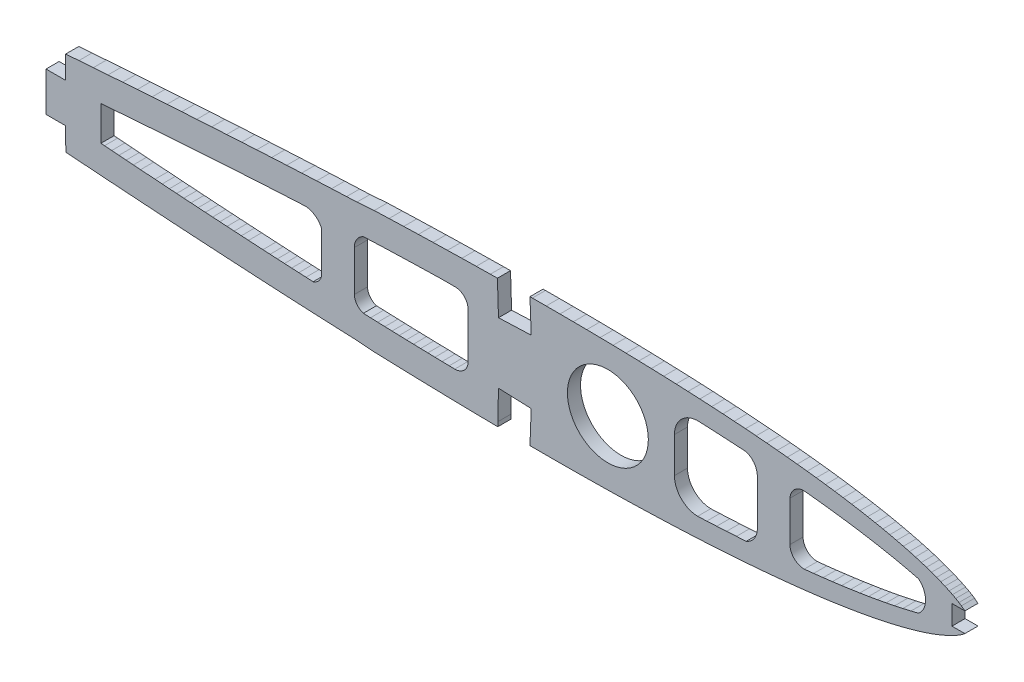
SolidWorks part; units mm, degrees
ref_plane "前视基准面" through (0, 0, 0) normal (0, 0, 1) x (1, 0, 0)
ref_plane "上视基准面" through (0, 0, 0) normal (0, 1, 0) x (1, 0, 0)
ref_plane "右视基准面" through (0, 0, 0) normal (1, 0, 0) x (0, 0, -1)
sketch "Model" plane through (0, 0, 0) normal (0, 0, 1) x (1, 0, 0)
  line L0 (131.5025, 16.1878) -> (129.5305, 16.1878)
  line L1 (129.5305, 16.1878) -> (129.5305, 13.1878)
  line L2 (129.5305, 13.1878) -> (131.5025, 13.1878)
  line L3 (60.157, 24.4938) -> (60.3185, 19.3451)
  line L4 (60.3185, 19.3451) -> (65.3145, 19.5391)
  line L5 (65.3145, 19.5391) -> (65.1226, 24.5339)
  line L6 (60.2125, 4.8817) -> (60.2125, 5.5444)
  line L7 (60.2125, 5.5444) -> (60.3179, 10.0318)
  line L8 (60.3179, 10.0318) -> (65.3139, 9.8388)
  line L9 (65.3139, 9.8388) -> (65.1209, 4.8418)
  line L10 (-5.7395, 21.1711) -> (-3.7144, 21.3221)
  line L11 (-3.7144, 21.3221) -> (-1.5144, 21.4831)
  line L12 (-1.5144, 21.4831) -> (0.7226, 21.6431)
  line L13 (0.7226, 21.6431) -> (2.9586, 21.8011)
  line L14 (2.9586, 21.8011) -> (5.1956, 21.9561)
  line L15 (5.1956, 21.9561) -> (7.4586, 22.1101)
  line L16 (7.4586, 22.1101) -> (9.7206, 22.2601)
  line L17 (9.7206, 22.2601) -> (11.9836, 22.4061)
  line L18 (11.9836, 22.4061) -> (14.2656, 22.5491)
  line L19 (14.2656, 22.5491) -> (16.5466, 22.6871)
  line L20 (16.5466, 22.6871) -> (18.8296, 22.8221)
  line L21 (18.8296, 22.8221) -> (21.1186, 22.9561)
  line L22 (21.1186, 22.9561) -> (23.4086, 23.0871)
  line L23 (23.4086, 23.0871) -> (25.6986, 23.2141)
  line L24 (25.6986, 23.2141) -> (27.9886, 23.3351)
  line L25 (27.9886, 23.3351) -> (30.2776, 23.4511)
  line L26 (30.2776, 23.4511) -> (32.5676, 23.5621)
  line L27 (32.5676, 23.5621) -> (34.8496, 23.6671)
  line L28 (34.8496, 23.6671) -> (37.1306, 23.7671)
  line L29 (37.1306, 23.7671) -> (38.7147, 23.833)
  line L30 (38.7147, 23.833) -> (41.3505, 24.0328)
  line L31 (41.3505, 24.0328) -> (43.6135, 24.1108)
  line L32 (43.6135, 24.1108) -> (45.8505, 24.1828)
  line L33 (45.8505, 24.1828) -> (48.0865, 24.2488)
  line L34 (48.0865, 24.2488) -> (50.3235, 24.3078)
  line L35 (50.3235, 24.3078) -> (52.5235, 24.3608)
  line L36 (52.5235, 24.3608) -> (54.7235, 24.4078)
  line L37 (54.7235, 24.4078) -> (56.9235, 24.4478)
  line L38 (56.9235, 24.4478) -> (59.0795, 24.4808)
  line L39 (59.0795, 24.4808) -> (60.157, 24.4938)
  line L40 (65.1226, 24.5339) -> (65.4935, 24.5358)
  line L41 (65.4935, 24.5358) -> (67.5965, 24.5398)
  line L42 (67.5965, 24.5398) -> (69.6995, 24.5358)
  line L43 (69.6995, 24.5358) -> (71.7415, 24.5248)
  line L44 (71.7415, 24.5248) -> (73.7825, 24.5058)
  line L45 (73.7825, 24.5058) -> (75.8245, 24.4788)
  line L46 (75.8245, 24.4788) -> (77.7965, 24.4448)
  line L47 (77.7965, 24.4448) -> (79.7685, 24.4018)
  line L48 (79.7685, 24.4018) -> (81.7395, 24.3498)
  line L49 (81.7395, 24.3498) -> (83.6355, 24.2918)
  line L50 (83.6355, 24.2918) -> (85.5305, 24.2248)
  line L51 (85.5305, 24.2248) -> (87.4255, 24.1488)
  line L52 (87.4255, 24.1488) -> (89.2365, 24.0668)
  line L53 (89.2365, 24.0668) -> (91.0465, 23.9758)
  line L54 (91.0465, 23.9758) -> (92.8565, 23.8748)
  line L55 (92.8565, 23.8748) -> (94.5765, 23.7688)
  line L56 (94.5765, 23.7688) -> (96.2945, 23.6538)
  line L57 (96.2945, 23.6538) -> (98.0125, 23.5268)
  line L58 (98.0125, 23.5268) -> (99.6345, 23.3978)
  line L59 (99.6345, 23.3978) -> (101.2535, 23.2578)
  line L60 (101.2535, 23.2578) -> (102.8735, 23.1068)
  line L61 (102.8735, 23.1068) -> (104.3905, 22.9548)
  line L62 (104.3905, 22.9548) -> (105.9065, 22.7928)
  line L63 (105.9065, 22.7928) -> (107.4205, 22.6188)
  line L64 (107.4205, 22.6188) -> (108.8265, 22.4458)
  line L65 (108.8265, 22.4458) -> (110.2305, 22.2608)
  line L66 (110.2305, 22.2608) -> (111.6335, 22.0628)
  line L67 (111.6335, 22.0628) -> (112.9235, 21.8688)
  line L68 (112.9235, 21.8688) -> (114.2105, 21.6628)
  line L69 (114.2105, 21.6628) -> (115.4955, 21.4438)
  line L70 (115.4955, 21.4438) -> (116.6655, 21.2318)
  line L71 (116.6655, 21.2318) -> (117.8315, 21.0068)
  line L72 (117.8315, 21.0068) -> (118.9955, 20.7678)
  line L73 (118.9955, 20.7678) -> (120.0385, 20.5388)
  line L74 (120.0385, 20.5388) -> (121.0785, 20.2958)
  line L75 (121.0785, 20.2958) -> (122.1155, 20.0388)
  line L76 (122.1155, 20.0388) -> (123.0305, 19.7978)
  line L77 (123.0305, 19.7978) -> (123.9415, 19.5428)
  line L78 (123.9415, 19.5428) -> (124.8475, 19.2708)
  line L79 (124.8475, 19.2708) -> (125.6295, 19.0188)
  line L80 (125.6295, 19.0188) -> (126.4055, 18.7518)
  line L81 (126.4055, 18.7518) -> (127.1755, 18.4648)
  line L82 (127.1755, 18.4648) -> (127.8215, 18.2068)
  line L83 (127.8215, 18.2068) -> (128.4605, 17.9328)
  line L84 (128.4605, 17.9328) -> (129.0925, 17.6428)
  line L85 (129.0925, 17.6428) -> (129.6015, 17.3938)
  line L86 (129.6015, 17.3938) -> (130.1025, 17.1288)
  line L87 (130.1025, 17.1288) -> (130.5915, 16.8418)
  line L88 (130.5915, 16.8418) -> (130.9655, 16.5968)
  line L89 (130.9655, 16.5968) -> (131.5025, 16.1878)
  line L92 (131.5025, 13.1878) -> (131.3255, 13.0418)
  line L93 (131.3255, 13.0418) -> (130.9655, 12.7788)
  line L94 (130.9655, 12.7788) -> (130.5915, 12.5348)
  line L95 (130.5915, 12.5348) -> (130.1025, 12.2478)
  line L96 (130.1025, 12.2478) -> (129.6015, 11.9828)
  line L97 (129.6015, 11.9828) -> (129.0925, 11.7338)
  line L98 (129.0925, 11.7338) -> (128.4605, 11.4438)
  line L99 (128.4605, 11.4438) -> (127.8215, 11.1698)
  line L100 (127.8215, 11.1698) -> (127.1755, 10.9108)
  line L101 (127.1755, 10.9108) -> (126.4055, 10.6248)
  line L102 (126.4055, 10.6248) -> (125.6295, 10.3568)
  line L103 (125.6295, 10.3568) -> (124.8475, 10.1058)
  line L104 (124.8475, 10.1058) -> (123.9415, 9.8338)
  line L105 (123.9415, 9.8338) -> (123.0305, 9.5788)
  line L106 (123.0305, 9.5788) -> (122.1155, 9.3378)
  line L107 (122.1155, 9.3378) -> (121.0785, 9.0798)
  line L108 (121.0785, 9.0798) -> (120.0385, 8.8378)
  line L109 (120.0385, 8.8378) -> (118.9955, 8.6088)
  line L110 (118.9955, 8.6088) -> (117.8315, 8.3688)
  line L111 (117.8315, 8.3688) -> (116.6655, 8.1448)
  line L112 (116.6655, 8.1448) -> (115.4955, 7.9328)
  line L113 (115.4955, 7.9328) -> (114.2105, 7.7128)
  line L114 (114.2105, 7.7128) -> (112.9235, 7.5068)
  line L115 (112.9235, 7.5068) -> (111.6335, 7.3128)
  line L116 (111.6335, 7.3128) -> (110.2305, 7.1158)
  line L117 (110.2305, 7.1158) -> (108.8265, 6.9308)
  line L118 (108.8265, 6.9308) -> (107.4205, 6.7568)
  line L119 (107.4205, 6.7568) -> (105.9065, 6.5828)
  line L120 (105.9065, 6.5828) -> (104.3905, 6.4208)
  line L121 (104.3905, 6.4208) -> (102.8735, 6.2688)
  line L122 (102.8735, 6.2688) -> (101.2535, 6.1188)
  line L123 (101.2535, 6.1188) -> (99.6345, 5.9788)
  line L124 (99.6345, 5.9788) -> (98.0125, 5.8488)
  line L125 (98.0125, 5.8488) -> (96.2945, 5.7228)
  line L126 (96.2945, 5.7228) -> (94.5765, 5.6068)
  line L127 (94.5765, 5.6068) -> (92.8565, 5.5008)
  line L128 (92.8565, 5.5008) -> (91.0465, 5.3998)
  line L129 (91.0465, 5.3998) -> (89.2365, 5.3088)
  line L130 (89.2365, 5.3088) -> (87.4255, 5.2278)
  line L131 (87.4255, 5.2278) -> (85.5305, 5.1518)
  line L132 (85.5305, 5.1518) -> (83.6355, 5.0848)
  line L133 (83.6355, 5.0848) -> (81.7395, 5.0258)
  line L134 (81.7395, 5.0258) -> (79.7685, 4.9748)
  line L135 (79.7685, 4.9748) -> (77.7965, 4.9318)
  line L136 (77.7965, 4.9318) -> (75.8245, 4.8968)
  line L137 (75.8245, 4.8968) -> (73.7825, 4.8698)
  line L138 (73.7825, 4.8698) -> (71.7415, 4.8508)
  line L139 (71.7415, 4.8508) -> (69.6995, 4.8398)
  line L140 (69.6995, 4.8398) -> (67.5965, 4.8368)
  line L141 (67.5965, 4.8368) -> (65.4935, 4.8398)
  line L142 (65.4935, 4.8398) -> (65.1209, 4.8418)
  line L143 (60.2125, 4.8817) -> (59.0795, 4.8948)
  line L144 (59.0795, 4.8948) -> (56.9235, 4.9278)
  line L145 (56.9235, 4.9278) -> (54.7235, 4.9678)
  line L146 (54.7235, 4.9678) -> (52.5235, 5.0148)
  line L147 (52.5235, 5.0148) -> (50.3235, 5.0678)
  line L148 (50.3235, 5.0678) -> (48.0865, 5.1278)
  line L149 (48.0865, 5.1278) -> (45.8505, 5.1928)
  line L150 (45.8505, 5.1928) -> (43.6135, 5.2648)
  line L151 (43.6135, 5.2648) -> (41.3505, 5.3428)
  line L152 (41.3505, 5.3428) -> (38.805, 5.5444)
  line L153 (38.805, 5.5444) -> (37.1306, 5.6141)
  line L154 (37.1306, 5.6141) -> (34.8496, 5.7131)
  line L155 (34.8496, 5.7131) -> (32.5676, 5.8181)
  line L156 (32.5676, 5.8181) -> (30.2776, 5.9291)
  line L157 (30.2776, 5.9291) -> (27.9886, 6.0451)
  line L158 (27.9886, 6.0451) -> (25.6986, 6.1661)
  line L159 (25.6986, 6.1661) -> (23.4086, 6.2931)
  line L160 (23.4086, 6.2931) -> (21.1186, 6.4241)
  line L161 (21.1186, 6.4241) -> (18.8296, 6.5581)
  line L162 (18.8296, 6.5581) -> (16.5466, 6.6931)
  line L163 (16.5466, 6.6931) -> (14.2656, 6.8321)
  line L164 (14.2656, 6.8321) -> (11.9836, 6.9741)
  line L165 (11.9836, 6.9741) -> (9.7206, 7.1201)
  line L166 (9.7206, 7.1201) -> (7.4586, 7.2711)
  line L167 (7.4586, 7.2711) -> (5.1956, 7.4251)
  line L168 (5.1956, 7.4251) -> (2.9586, 7.5801)
  line L169 (2.9586, 7.5801) -> (0.7226, 7.7371)
  line L170 (0.7226, 7.7371) -> (-1.5144, 7.8971)
  line L171 (-1.5144, 7.8971) -> (-3.7144, 8.0591)
  line L172 (-3.7144, 8.0591) -> (-5.7204, 8.2086)
  line L173 (124.4378, 12.3496) -> (123.2638, 12.0561)
  line L174 (123.2638, 12.0561) -> (122.0252, 11.77)
  line L175 (122.0252, 11.77) -> (120.7739, 11.5)
  line L176 (120.7739, 11.5) -> (119.4759, 11.2404)
  line L177 (119.4759, 11.2404) -> (118.1618, 10.9947)
  line L178 (118.1618, 10.9947) -> (116.8167, 10.7589)
  line L179 (116.8167, 10.7589) -> (115.4678, 10.5396)
  line L180 (115.4678, 10.5396) -> (114.0848, 10.3308)
  line L181 (114.0848, 10.3308) -> (112.6926, 10.1334)
  line L182 (112.6926, 10.1334) -> (111.2807, 9.9462)
  line L183 (111.2807, 9.9462) -> (109.8651, 9.7714)
  line L184 (109.8651, 9.7714) -> (108.4269, 9.6062)
  line L185 (108.4269, 9.6062) -> (106.9832, 9.4509)
  line L186 (98.1351, 8.7056) -> (96.6346, 8.6104)
  line L187 (96.6346, 8.6104) -> (95.1268, 8.5212)
  line L188 (95.1268, 8.5212) -> (93.619, 8.4386)
  line L189 (93.619, 8.4386) -> (92.1045, 8.3642)
  line L190 (92.1045, 8.3642) -> (90.7113, 8.2999)
  line L191 (87.1711, 11.9028) -> (87.1711, 17.3338)
  line L192 (90.7113, 20.9367) -> (92.1045, 20.8724)
  line L193 (92.1045, 20.8724) -> (93.619, 20.7981)
  line L194 (93.619, 20.7981) -> (95.1268, 20.7155)
  line L195 (95.1268, 20.7155) -> (96.6346, 20.6263)
  line L196 (96.6346, 20.6263) -> (98.1351, 20.531)
  line L197 (106.9832, 19.7857) -> (108.4269, 19.6304)
  line L198 (108.4269, 19.6304) -> (109.8651, 19.4653)
  line L199 (109.8651, 19.4653) -> (111.2807, 19.2904)
  line L200 (111.2807, 19.2904) -> (112.6926, 19.1032)
  line L201 (112.6926, 19.1032) -> (114.0848, 18.9058)
  line L202 (114.0848, 18.9058) -> (115.4678, 18.697)
  line L203 (115.4678, 18.697) -> (116.8167, 18.4777)
  line L204 (116.8167, 18.4777) -> (118.1618, 18.2419)
  line L205 (118.1618, 18.2419) -> (119.4759, 17.9963)
  line L206 (119.4759, 17.9963) -> (120.7739, 17.7367)
  line L207 (120.7739, 17.7367) -> (122.0252, 17.4667)
  line L208 (122.0252, 17.4667) -> (123.2638, 17.1805)
  line L209 (123.2638, 17.1805) -> (124.4378, 16.887)
  line L211 (-5.7395, 21.1711) -> (-5.7395, 17.6899)
  line L212 (-5.7395, 17.6899) -> (-8.7395, 17.6899)
  line L213 (-8.7395, 17.6899) -> (-8.7395, 11.6899)
  line L214 (-8.7395, 11.6899) -> (-5.7395, 11.6899)
  line L215 (-5.7395, 11.6899) -> (-5.7204, 8.2086)
  line L216 (-0.3573, 12.064) -> (0.1946, 12.0208)
  line L217 (0.1946, 12.0208) -> (1.292, 11.9361)
  line L218 (1.292, 11.9361) -> (2.391, 11.8523)
  line L219 (2.391, 11.8523) -> (3.4938, 11.7695)
  line L220 (3.4938, 11.7695) -> (4.5947, 11.6857)
  line L221 (4.5947, 11.6857) -> (5.6919, 11.6045)
  line L222 (5.6919, 11.6045) -> (6.7928, 11.5242)
  line L223 (6.7928, 11.5242) -> (7.8938, 11.444)
  line L224 (7.8938, 11.444) -> (8.9916, 11.365)
  line L225 (8.9916, 11.365) -> (10.0924, 11.2872)
  line L226 (10.0924, 11.2872) -> (11.1905, 11.2094)
  line L227 (11.1905, 11.2094) -> (12.2883, 11.1341)
  line L228 (12.2883, 11.1341) -> (13.3891, 11.0586)
  line L229 (13.3891, 11.0586) -> (14.487, 10.9845)
  line L230 (14.487, 10.9845) -> (15.5848, 10.9115)
  line L231 (15.5848, 10.9115) -> (16.6828, 10.8398)
  line L232 (16.6828, 10.8398) -> (17.7794, 10.7692)
  line L233 (17.7794, 10.7692) -> (18.8771, 10.6999)
  line L234 (18.8771, 10.6999) -> (19.9768, 10.6316)
  line L235 (19.9768, 10.6316) -> (21.0735, 10.5634)
  line L236 (21.0735, 10.5634) -> (22.1694, 10.4978)
  line L237 (22.1694, 10.4978) -> (23.268, 10.4331)
  line L238 (23.268, 10.4331) -> (24.3646, 10.3685)
  line L239 (24.3646, 10.3685) -> (25.4593, 10.3064)
  line L240 (25.4593, 10.3064) -> (26.5559, 10.2454)
  line L241 (26.5559, 10.2454) -> (27.6525, 10.1856)
  line L242 (27.6525, 10.1856) -> (28.7472, 10.1271)
  line L243 (28.7472, 10.1271) -> (29.8438, 10.0709)
  line L244 (29.8438, 10.0709) -> (30.9393, 10.0147)
  line L245 (30.9393, 10.0147) -> (32.0339, 9.961)
  line L246 (39.6986, 9.6228) -> (40.7909, 9.581)
  line L247 (40.7909, 9.581) -> (41.8844, 9.5404)
  line L248 (41.8844, 9.5404) -> (42.9767, 9.5022)
  line L249 (42.9767, 9.5022) -> (44.069, 9.4652)
  line L250 (44.069, 9.4652) -> (45.1612, 9.4306)
  line L251 (45.1612, 9.4306) -> (46.2554, 9.3971)
  line L252 (46.2554, 9.3971) -> (47.3458, 9.365)
  line L253 (47.3458, 9.365) -> (48.435, 9.3364)
  line L254 (48.435, 9.3364) -> (49.5281, 9.3088)
  line L255 (49.5281, 9.3088) -> (50.6179, 9.2826)
  line L256 (50.6179, 9.2826) -> (51.7071, 9.2588)
  line L257 (51.7071, 9.2588) -> (52.795, 9.2373)
  line L258 (52.795, 9.2373) -> (53.6463, 9.2224)
  line L259 (55.6814, 11.2221) -> (55.6814, 18.1211)
  line L260 (53.6814, 20.1211) -> (51.7064, 20.1211)
  line L261 (51.7064, 20.1211) -> (50.6179, 20.0972)
  line L262 (50.6179, 20.0972) -> (49.5281, 20.071)
  line L263 (49.5281, 20.071) -> (48.435, 20.0435)
  line L264 (48.435, 20.0435) -> (47.3458, 20.0149)
  line L265 (47.3458, 20.0149) -> (46.2554, 19.9827)
  line L266 (46.2554, 19.9827) -> (45.1612, 19.9492)
  line L267 (45.1612, 19.9492) -> (44.069, 19.9146)
  line L268 (44.069, 19.9146) -> (42.9767, 19.8776)
  line L269 (42.9767, 19.8776) -> (41.8844, 19.8394)
  line L270 (41.8844, 19.8394) -> (40.7909, 19.7988)
  line L271 (40.7909, 19.7988) -> (39.6986, 19.757)
  line L272 (30.9393, 19.3651) -> (29.8438, 19.3089)
  line L273 (29.8438, 19.3089) -> (28.7472, 19.2527)
  line L274 (28.7472, 19.2527) -> (27.6525, 19.1942)
  line L275 (27.6525, 19.1942) -> (26.5559, 19.1344)
  line L276 (26.5559, 19.1344) -> (25.4593, 19.0734)
  line L277 (25.4593, 19.0734) -> (24.3646, 19.0113)
  line L278 (24.3646, 19.0113) -> (23.268, 18.9468)
  line L279 (23.268, 18.9468) -> (22.1694, 18.8821)
  line L280 (22.1694, 18.8821) -> (21.0735, 18.8164)
  line L281 (21.0735, 18.8164) -> (19.9768, 18.7482)
  line L282 (19.9768, 18.7482) -> (18.8771, 18.68)
  line L283 (18.8771, 18.68) -> (17.7794, 18.6106)
  line L284 (17.7794, 18.6106) -> (16.6828, 18.54)
  line L285 (16.6828, 18.54) -> (15.5848, 18.4683)
  line L286 (15.5848, 18.4683) -> (14.487, 18.3953)
  line L287 (14.487, 18.3953) -> (13.3891, 18.3212)
  line L288 (13.3891, 18.3212) -> (12.2883, 18.2457)
  line L289 (12.2883, 18.2457) -> (11.1905, 18.1704)
  line L290 (11.1905, 18.1704) -> (10.0924, 18.0926)
  line L291 (10.0924, 18.0926) -> (8.9916, 18.0148)
  line L292 (8.9916, 18.0148) -> (7.8938, 17.9358)
  line L293 (7.8938, 17.9358) -> (6.7928, 17.8556)
  line L294 (6.7928, 17.8556) -> (5.6919, 17.7753)
  line L295 (5.6919, 17.7753) -> (4.5947, 17.6941)
  line L296 (4.5947, 17.6941) -> (3.4938, 17.6103)
  line L297 (3.4938, 17.6103) -> (2.391, 17.5275)
  line L298 (2.391, 17.5275) -> (1.292, 17.4438)
  line L299 (1.292, 17.4438) -> (0.1946, 17.359)
  line L300 (0.1946, 17.359) -> (-0.3573, 17.3342)
  line L301 (-0.3573, 12.064) -> (-0.3573, 17.3342)
  line L302 (38.3181, 17.6236) -> (38.3181, 11.4187)
  line L303 (99.82, 18.2792) -> (99.82, 11.0668)
  line L304 (33.323, 17.621) -> (33.323, 11.4187)
  line L305 (104.8029, 17.736) -> (104.8029, 11.6088)
  arc A0 (124.4378, 12.3496) -> (124.4378, 16.887) centre (122.5373, 14.6183) ccw
  circle A1 centre (77.0124, 14.6878) radius 6.1745
  arc A2 (32.0339, 9.961) -> (33.323, 11.4187) centre (31.4988, 11.733) ccw
  arc A3 (38.3181, 11.4187) -> (39.6986, 9.6228) centre (40.2691, 11.4899) ccw
  arc A4 (39.6986, 19.757) -> (38.3181, 17.6236) centre (40.6588, 17.6223) ccw
  arc A5 (33.323, 17.621) -> (30.9393, 19.3651) centre (30.7139, 16.5561) ccw
  arc A6 (98.1351, 8.7056) -> (99.82, 11.0668) centre (97.1119, 11.2175) ccw
  arc A7 (104.8029, 11.6088) -> (106.9832, 9.4509) centre (106.9696, 11.6176) ccw
  arc A8 (99.82, 18.2792) -> (98.1351, 20.531) centre (97.3387, 18.1789) ccw
  arc A9 (106.9832, 19.7857) -> (104.8029, 17.736) centre (106.9394, 17.6478) ccw
  arc A10 (87.1711, 11.9028) -> (90.7113, 8.2999) centre (90.7746, 11.9028) ccw
  arc A11 (90.7113, 20.9367) -> (87.1711, 17.3338) centre (90.7746, 17.3338) ccw
  arc A12 (53.6463, 9.2224) -> (55.6814, 11.2221) centre (53.6814, 11.2221) ccw
  arc A13 (55.6814, 18.1211) -> (53.6814, 20.1211) centre (53.6814, 18.1211) ccw
  point P13 (60.2125, 5.5444)
  point P45 (60.3179, 4.8817)
  point P48 (38.3181, 18.0148)
  point P49 (60.2093, 4.8471)
  point P135 (0, 0)
  point P136 (131.5058, 16.1876)
  point P137 (131.5025, 16.2881)
  point P251 (0, 0)
  point P256 (130.5915, 14.9027)
  point P337 (65.1226, 24.785)
  point P341 (131.5037, 16.1761)
  point P342 (60.3185, 24.4938)
  point P343 (-0.3573, 12.0208)
  point P344 (131.5126, 16.1878)
  point P345 (0, 0)
  point P346 (0, 0)
  point P347 (0, 0)
  point P348 (0, 0)
  point P349 (131.6176, 16.1878)
  point P350 (0, 0)
  point P351 (131.5058, 16.3232)
  point P352 (131.5025, 16.1878)
  point P353 (0, 17.7753)
extrude "凸台-拉伸1" add sketch "Model" along normal blind 2
